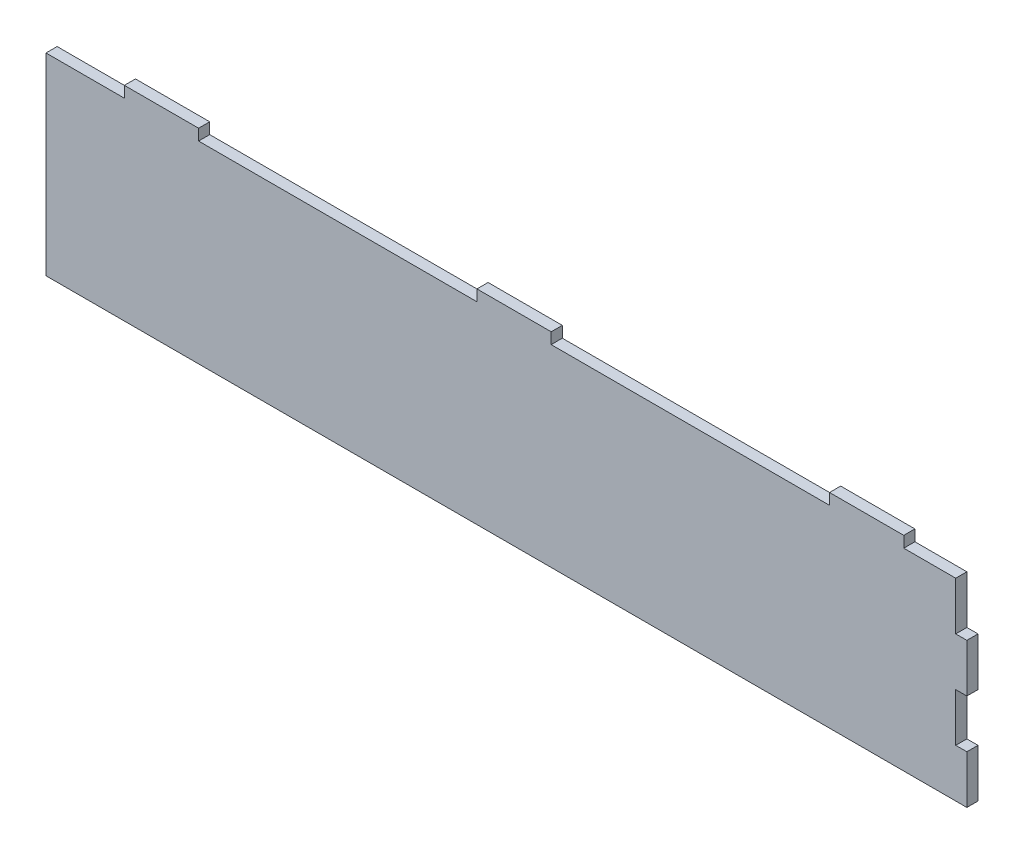
SolidWorks part; units mm, degrees
ref_plane "Front Plane" through (0, 0, 0) normal (0, 0, 1) x (1, 0, 0)
ref_plane "Top Plane" through (0, 0, 0) normal (0, 1, 0) x (1, 0, 0)
ref_plane "Right Plane" through (0, 0, 0) normal (1, 0, 0) x (0, 0, -1)
sketch "Sketch1" plane through (0, 0, 0) normal (0, 0, 1) x (1, 0, 0)
  line L0 (-124.555, 24.5364) -> (-103.445, 24.5364)
  line L1 (-103.445, 27.5364) -> (-83.445, 27.5364)
  line L3 (-124.555, -27.4636) -> (123.555, -27.4636)
  line L4 (123.555, 11.5364) -> (123.555, -1.4636)
  line L5 (-127.3833, 28.3146) -> (123.555, -27.4636) construction
  line L6 (-125.555, -27.5) -> (125.555, 27.5) construction
  line L7 (-103.445, 27.5364) -> (-103.445, 24.5364)
  line L8 (-83.445, 27.5364) -> (-83.445, 24.5364)
  line L9 (-8.445, 27.5364) -> (-8.445, 24.5364)
  line L10 (106.555, 27.5364) -> (106.555, 24.5364)
  line L11 (11.555, 27.5364) -> (11.555, 24.5364)
  line L12 (86.555, 27.5364) -> (86.555, 24.5364)
  line L13 (-83.445, 24.5364) -> (-8.445, 24.5364)
  line L14 (-8.445, 27.5364) -> (11.555, 27.5364)
  line L15 (11.555, 24.5364) -> (86.555, 24.5364)
  line L16 (86.555, 27.5364) -> (106.555, 27.5364)
  line L17 (106.555, 24.5364) -> (120.555, 24.5364)
  line L19 (-124.555, 24.5364) -> (-124.555, -27.4636)
  line L23 (120.555, 11.5364) -> (123.555, 11.5364)
  line L24 (120.555, -1.4636) -> (123.555, -1.4636)
  line L25 (120.555, -14.4636) -> (123.555, -14.4636)
  line L29 (120.555, 11.5364) -> (120.555, 24.5364)
  line L30 (123.555, -14.4636) -> (123.555, -27.4636)
  line L31 (120.555, -14.4636) -> (120.555, -1.4636)
  point P0 (0, 0)
  dimension "D1" = 249.11
  dimension "D2" = 55
  dimension "D3" = 3
  dimension "D4" = 21.11
  dimension "D5" = 20
  dimension "D6" = 75
  dimension "D7" = 20
  dimension "D8" = 75
  dimension "D9" = 20
  dimension "D10" = 17
  dimension "D14" = 13
  dimension "D17" = 55
  dimension "D15" = 3
extrude "Boss-Extrude1" add sketch "Sketch1" along normal blind 3
